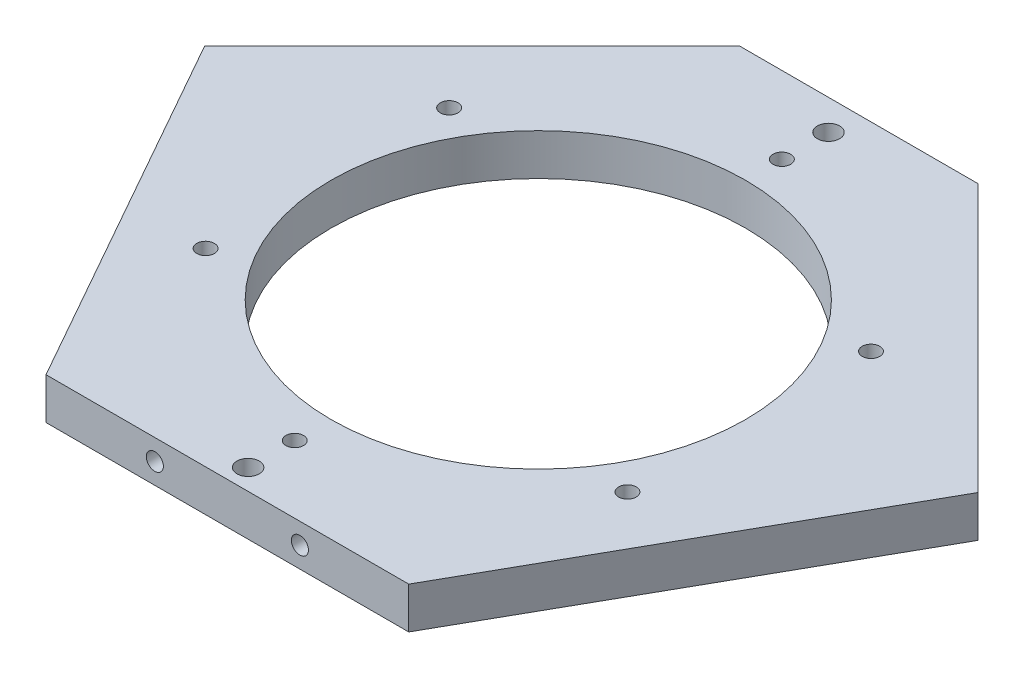
SolidWorks part; units mm, degrees
material "1060 合金"
ref_plane "前视基准面" through (0, 0, 0) normal (0, 0, 1) x (1, 0, 0)
ref_plane "上视基准面" through (0, 0, 0) normal (0, 1, 0) x (1, 0, 0)
ref_plane "右视基准面" through (0, 0, 0) normal (1, 0, 0) x (0, 0, -1)
sketch "草图2" plane through (0, 0, 0) normal (0, 1, 0) x (1, 0, 0)
  line L0 (0, 0) -> (0, 84.0702) construction
  line L7 (23, 61.8528) -> (-23, 61.8528)
  line L8 (-23, 61.8528) -> (-74.6188, 10.234)
  line L9 (-74.6188, 10.234) -> (-35, -60)
  line L10 (-35, -60) -> (35, -60)
  line L11 (35, -60) -> (74.6188, 10.234)
  line L12 (74.6188, 10.234) -> (23, 61.8528)
  circle A0 centre (0, 0) radius 40
  point P0 (0, 0)
  dimension "D3" = 80
  dimension "D1" = 73
  dimension "D2" = 60
  dimension "D4" = 70
  dimension "D5" = 60
  dimension "D6" = 46
extrude "凸台-拉伸1" add sketch "草图2" along normal mid plane 8
hole_wizard "M5 间隙孔1" [suppressed] positions "草图4" profile "草图3" hole size "M5" standard "GB"
sketch "草图4" plane through (0, 2.4, 0) normal (0, 1, 0) x (1, 0, 0)
  line L1 (-50, 50) -> (50, 50)
  line L2 (-50, 50) -> (-50, -50)
  line L3 (-50, -50) -> (50, -50)
  line L4 (50, 50) -> (50, -50)
  line L5 (-50, 50) -> (50, -50) construction
  line L6 (-50, -50) -> (50, 50) construction
  point P0 (-50, 50)
  point P4 (50, -50)
  point P72 (-50, -50)
  point P73 (50, 50)
  dimension "D1" = 100
sketch "草图3" plane through (-50, 2.4, -50) normal (1, 0, 0) x (0, 0, 1)
  line L0 (0, 0) -> (0, 4.8)
  line L1 (0, 4.8) -> (2.9, 4.8)
  line L2 (2.9, 4.8) -> (2.9, 0)
  line L5 (2.9, 0) -> (0, 0)
  line L11 (0, -6.35) -> (0, 107.95) construction
  dimension "通孔孔直径" = 5.8
  dimension "通孔孔深度" = 4.8
hole_wizard "M3 间隙孔1" positions "草图6" profile "草图5" hole size "M3" standard "GB" end condition through all
sketch "草图6" plane through (0, 4, 0) normal (0, 1, 0) x (1, 0, 0)
  line L0 (0, 0) -> (0, 47) construction
  point P0 (0, 47)
  point P9 (40.7032, 23.5)
  point P10 (40.7032, -23.5)
  point P11 (0, -47)
  point P12 (-40.7032, -23.5)
  point P13 (-40.7032, 23.5)
  dimension "D1" = 47
  dimension "D3" = 47
  dimension "D2" = 6
sketch "草图5" plane through (0, 4, -47) normal (1, 0, 0) x (0, 0, 1)
  line L0 (0, 0) -> (0, 8)
  line L1 (0, 8) -> (1.7, 8)
  line L2 (1.7, 8) -> (1.7, 0)
  line L5 (1.7, 0) -> (0, 0)
  line L11 (0, -6.35) -> (0, 107.95) construction
  dimension "通孔孔直径" = 3.4
  dimension "通孔孔深度" = 8
hole_wizard "M4 螺纹孔1" positions "草图8" profile "草图7" tap size "M4" standard "GB"
sketch "草图8" plane through (42.4264, 0, -42.4264) normal (0.7071, 0, -0.7071) x (-0.7071, 0, -0.7071)
  line L0 (-8.9, 0) -> (-8.9, 20.3728) construction
  line L3 (-45.5269, -4) -> (27.4731, -4) construction
  point P0 (5.1, 0)
  point P2 (-22.9, 0)
  dimension "D1" = 4
  dimension "D2" = 28
  dimension "D3" = 8.9
sketch "草图7" plane through (38.8202, 0, -46.0327) normal (0, 1, 0) x (-0.7071, 0, -0.7071)
  line L0 (0, 0) -> (0, 12.9914)
  line L1 (0, 12.9914) -> (1.65, 12)
  line L2 (1.65, 12) -> (1.65, 0)
  line L5 (1.65, 0) -> (0, 0)
  line L10 (0, 12.9914) -> (-1.65, 12) construction
  line L11 (0, -6.35) -> (0, 107.95) construction
  dimension "螺纹孔钻头直径" = 3.3
  dimension "螺纹孔钻头深度" = 12
  dimension "导头角度" = 118
cosmetic thread "孔螺蚊线1" parameters "D1"=11.3, "D2"=4
cosmetic thread "孔螺蚊线2" parameters "D1"=11.3, "D2"=4
mirror "镜向1" about plane through (0, 0, 0) normal (1, 0, 0) of "M4 螺纹孔1"
hole_wizard "M4 螺纹孔3" positions "草图16" profile "草图15" tap size "M4" standard "GB"
sketch "草图16" plane through (0, 0, 60) normal (0, 0, 1) x (1, 0, 0)
  line L0 (0, 0) -> (0, 17.9752) construction
  point P0 (14, 0)
  point P2 (-14, 0)
  dimension "D1" = 28
sketch "草图15" plane through (14, 0, 60) normal (1, 0, 0) x (0, -1, 0)
  line L0 (0, 0) -> (0, 15.9914)
  line L1 (0, 15.9914) -> (1.65, 15)
  line L2 (1.65, 15) -> (1.65, 0)
  line L5 (1.65, 0) -> (0, 0)
  line L10 (0, 15.9914) -> (-1.65, 15) construction
  line L11 (0, -6.35) -> (0, 107.95) construction
  dimension "螺纹孔钻头直径" = 3.3
  dimension "螺纹孔钻头深度" = 15
  dimension "导头角度" = 118
cosmetic thread "孔螺蚊线5" parameters "D1"=11, "D2"=4
cosmetic thread "孔螺蚊线6" parameters "D1"=11, "D2"=4
hole_wizard "M4 间隙孔1" [suppressed] positions "草图18" profile "草图17" hole size "M4" standard "GB"
sketch "草图18" plane through (0, 4, 0) normal (0, 1, 0) x (1, 0, 0)
  line L0 (20, 64.8528) -> (-20, 64.8528) construction
  line L1 (0, 64.8528) -> (0, 38.5211) construction
  point P0 (-7, 57.8528)
  point P5 (7, 57.8528)
  dimension "D1" = 7
  dimension "D2" = 14
sketch "草图17" plane through (-7, 4, -57.8528) normal (1, 0, 0) x (0, 0, 1)
  line L0 (0, 0) -> (0, 8)
  line L1 (0, 8) -> (2.15, 8)
  line L2 (2.15, 8) -> (2.15, 0)
  line L5 (2.15, 0) -> (0, 0)
  line L11 (0, -6.35) -> (0, 107.95) construction
  dimension "通孔孔直径" = 4.3
  dimension "通孔孔深度" = 8
hole_wizard "M4 间隙孔2" positions "草图20" profile "草图19" hole size "M4" standard "GB" end condition up to next
sketch "草图20" plane through (0, 4, 0) normal (0, 1, 0) x (1, 0, 0)
  point P0 (0, 56)
  point P2 (0, -56)
  dimension "D1" = 56
  dimension "D2" = 56
sketch "草图19" plane through (0, 4, -56) normal (1, 0, 0) x (0, 0, 1)
  line L0 (0, 0) -> (0, 8)
  line L1 (0, 8) -> (2.15, 8)
  line L2 (2.15, 8) -> (2.15, 0)
  line L5 (2.15, 0) -> (0, 0)
  line L11 (0, -6.35) -> (0, 107.95) construction
  dimension "通孔孔直径" = 4.3
  dimension "通孔孔深度" = 8
